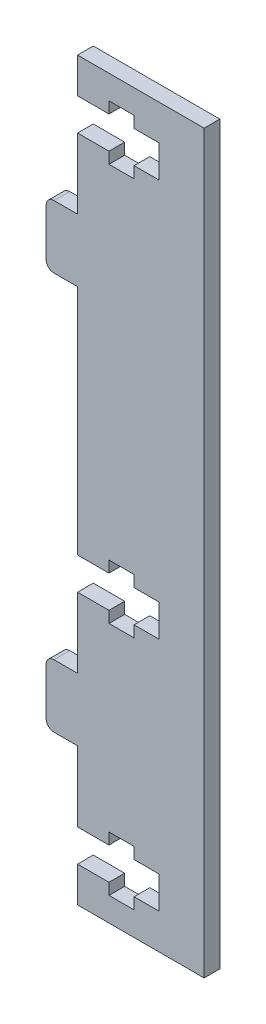
SolidWorks part; units mm, degrees
ref_plane "前视基准面" through (0, 0, 0) normal (0, 0, 1) x (1, 0, 0)
ref_plane "上视基准面" through (0, 0, 0) normal (0, 1, 0) x (1, 0, 0)
ref_plane "右视基准面" through (0, 0, 0) normal (1, 0, 0) x (0, 0, -1)
sketch "草图1" plane through (0, 0, 0) normal (0, 0, 1) x (1, 0, 0)
  line L0 (0, 121.6328) -> (0, -39.6672) construction
  line L1 (0, 38.9328) -> (4, 38.9328)
  line L6 (4, 38.9328) -> (4, 37.4828)
  line L7 (4, 37.4828) -> (7.2, 37.4828)
  line L12 (7.2, 37.4828) -> (7.2, 38.9328)
  line L13 (7.2, 38.9328) -> (10.4, 38.9328)
  line L14 (10.4, 38.9328) -> (10.4, 43.0328)
  line L15 (0, 40.9828) -> (10.4, 40.9828) construction
  line L16 (7.2, 43.0328) -> (10.4, 43.0328)
  line L17 (7.2, 44.4828) -> (7.2, 43.0328)
  line L18 (4, 44.4828) -> (7.2, 44.4828)
  line L19 (4, 43.0328) -> (4, 44.4828)
  line L20 (0, 43.0328) -> (4, 43.0328)
  line L21 (0, 43.0328) -> (0, 47.5328)
  line L22 (0, 47.5328) -> (16.1252, 47.5328)
  line L23 (16.1252, 47.5328) -> (16.1252, -46.2172)
  line L24 (16.1252, -46.2172) -> (0, -46.2172)
  line L25 (0, -41.7172) -> (4, -41.7172)
  line L26 (4, -41.7172) -> (4, -43.1672)
  line L27 (4, -43.1672) -> (7.2, -43.1672)
  line L28 (7.2, -43.1672) -> (7.2, -41.7172)
  line L29 (7.2, -41.7172) -> (10.4, -41.7172)
  line L30 (10.4, -41.7172) -> (10.4, -37.6172)
  line L31 (0, -39.6672) -> (10.4, -39.6672) construction
  line L32 (7.2, -37.6172) -> (10.4, -37.6172)
  line L33 (7.2, -36.1672) -> (7.2, -37.6172)
  line L34 (4, -36.1672) -> (7.2, -36.1672)
  line L35 (4, -37.6172) -> (4, -36.1672)
  line L36 (0, -37.6172) -> (4, -37.6172)
  line L37 (0, -28.6672) -> (-4, -28.6672)
  line L38 (-4, -28.6672) -> (-4, -20.6672)
  line L39 (-4, -20.6672) -> (0, -20.6672)
  line L40 (-4, -24.6672) -> (0, -24.6672) construction
  line L41 (0, -9.6672) -> (10.4, -9.6672) construction
  line L42 (0, -11.7172) -> (4, -11.7172)
  line L43 (4, -11.7172) -> (4, -13.1672)
  line L44 (4, -13.1672) -> (7.2, -13.1672)
  line L45 (7.2, -13.1672) -> (7.2, -11.7172)
  line L46 (7.2, -11.7172) -> (10.4, -11.7172)
  line L47 (10.4, -7.6172) -> (10.4, -11.7172)
  line L48 (7.2, -7.6172) -> (10.4, -7.6172)
  line L49 (7.2, -6.1672) -> (7.2, -7.6172)
  line L50 (4, -6.1672) -> (7.2, -6.1672)
  line L51 (4, -7.6172) -> (4, -6.1672)
  line L52 (0, -7.6172) -> (4, -7.6172)
  line L53 (0, -11.7172) -> (0, -20.6672)
  line L54 (0, -28.6672) -> (0, -37.6172)
  line L55 (0, 29.9828) -> (-4, 29.9828)
  line L56 (-4, 29.9828) -> (-4, 21.9828)
  line L57 (-4, 21.9828) -> (0, 21.9828)
  line L58 (-4, 25.9828) -> (0, 25.9828) construction
  line L59 (0, 38.9328) -> (0, 29.9828)
  line L60 (0, 21.9828) -> (0, -7.6172)
  line L61 (0, -41.7172) -> (0, -46.2172)
  point P35 (5.6, -43.1672)
  dimension "D2" = 4
  dimension "D5" = 4
  dimension "D1" = 80.65
  dimension "D3" = 3.2
  dimension "D4" = 2.05
  dimension "D6" = 3.2
  dimension "D7" = 7
  dimension "D8" = 4.1
  dimension "D9" = 7
  dimension "D10" = 15
  dimension "D11" = 4
  dimension "D12" = 8
  dimension "D13" = 15
  dimension "D14" = 8
  dimension "D15" = 4.5
extrude "凸台-拉伸1" add sketch "草图1" along normal blind 2 contours L23 L24 L61 L25 L26 L27 L28 L29 L30 L32 L33 L34 L35 L36 L54 L37 L38 L39 L53 L42 L43 L44 L45 L46 L47 L48 L49 L50 L51 L52 L60 L57 L56 L55 L59 L1 L6 L7 L12 L13 L14 L16 L17 L18 L19 L20 L21 L22
sketch "草图2" plane through (0, 0, 0) normal (-1, 0, 0) x (0, 0, 1)
  line L0 (1, -37.6172) -> (1, -41.7172)
  line L1 (2, -37.6172) -> (0, -37.6172) construction
  line L2 (2, -41.7172) -> (0, -41.7172) construction
  circle A0 centre (1, -39.6672) radius 2.05
fillet "圆角1" radius 1 4 edges at (-4, 29.9828, 1) (-4, 21.9828, 1) (-4, -20.6672, 1) (-4, -28.6672, 1)
